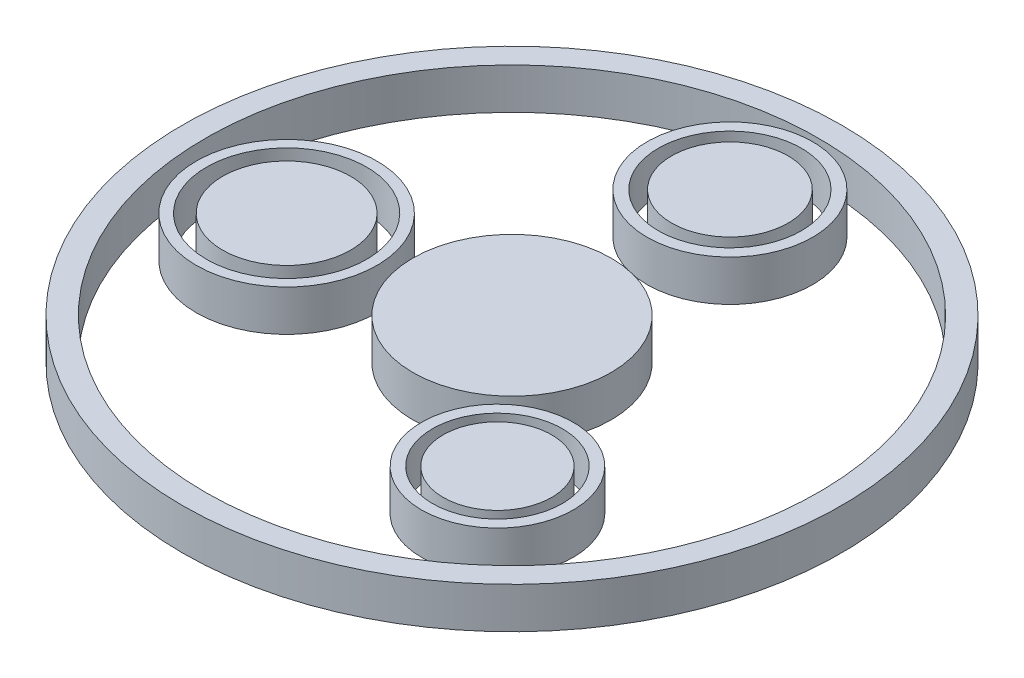
SolidWorks part; units mm, degrees
ref_plane "Front Plane" through (0, 0, 0) normal (0, 0, 1) x (1, 0, 0)
ref_plane "Top Plane" through (0, 0, 0) normal (0, 1, 0) x (1, 0, 0)
ref_plane "Right Plane" through (0, 0, 0) normal (1, 0, 0) x (0, 0, -1)
sketch "Sketch1" plane through (0, 0, 0) normal (0, 1, 0) x (1, 0, 0)
  circle A0 centre (0, 0) radius 74.6426
  circle A1 centre (0, 0) radius 24.135
  circle A2 centre (0, 0) radius 80.2226
  circle A3 centre (30.0233, -33.5715) radius 18.4776
  circle A4 centre (0, 53.0411) radius 17.4159
  circle A5 centre (-48.947, -5.9137) radius 22.002
  circle A6 centre (-48.947, -5.9137) radius 19.4798
  circle A7 centre (-48.947, -5.9137) radius 15.5764
  circle A8 centre (30.0233, -33.5715) radius 15.8011
  circle A9 centre (30.0233, -33.5715) radius 13.203
  circle A10 centre (0, 53.0411) radius 14.1812
  circle A11 centre (0, 53.0411) radius 20.1524
extrude "Boss-Extrude1" add sketch "Sketch1" along normal blind 10 contours A2 A0 | A1 | A7 | A5 A6 | A10 | A11 A4 | A9 | A3 A8
